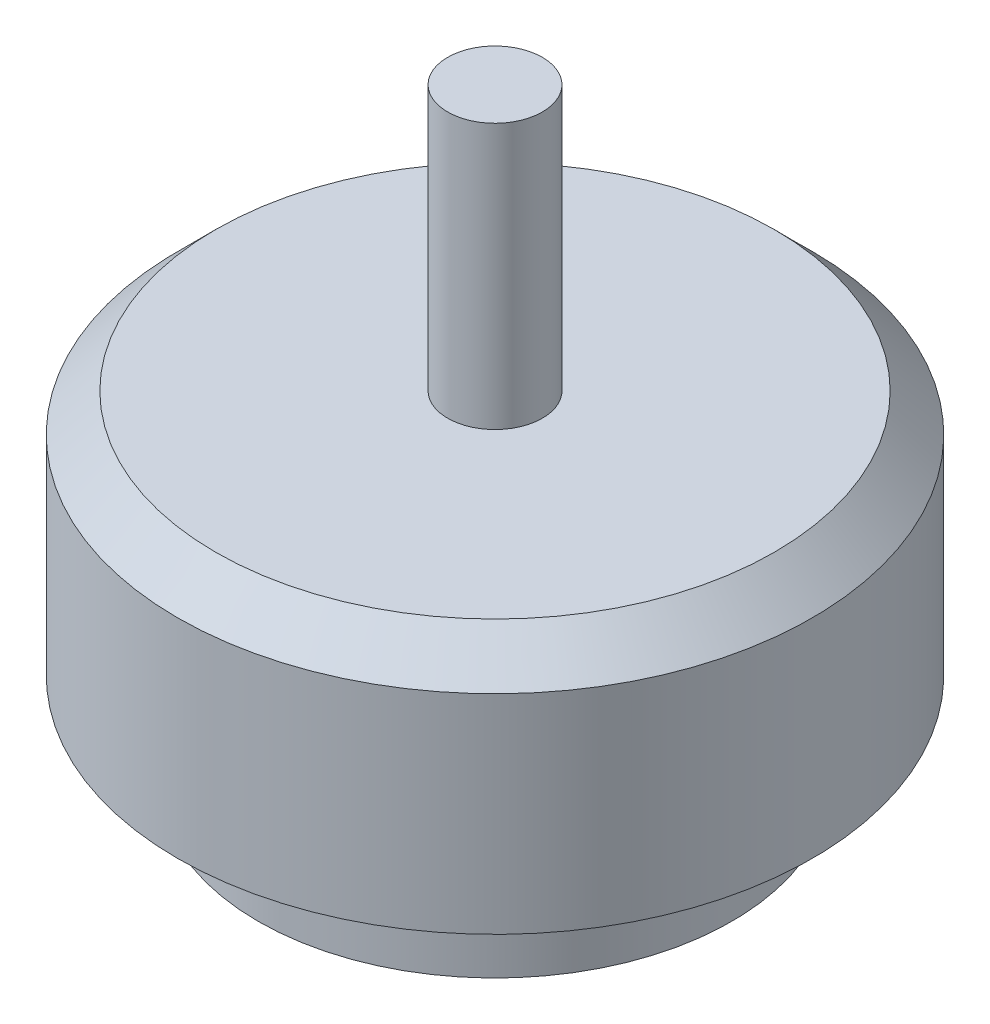
SolidWorks part; units mm, degrees
material "Custom Plastic"
ref_plane "Front Plane" through (0, 0, 0) normal (0, 0, 1) x (1, 0, 0)
ref_plane "Top Plane" through (0, 0, 0) normal (0, 1, 0) x (1, 0, 0)
ref_plane "Right Plane" through (0, 0, 0) normal (1, 0, 0) x (0, 0, -1)
sketch "Sketch1" plane through (0, 0, 0) normal (0, 0, 1) x (1, 0, 0)
  line L0 (0, 14) -> (2.5, 14)
  line L1 (2.5, 14) -> (2.5, 0)
  line L2 (2.5, 0) -> (16.75, 0)
  line L3 (16.75, 0) -> (16.75, -13)
  line L4 (16.75, -13) -> (5, -13)
  line L5 (5, -13) -> (5, -15)
  line L6 (5, -15) -> (12.5, -15)
  line L7 (12.5, -15) -> (12.5, -18)
  line L8 (12.5, -18) -> (0, -18)
  line L9 (0, -18) -> (0, 14) construction
  line L10 (0, 14) -> (0, -18)
  dimension "D1" = 14
  dimension "D2" = 27
  dimension "D3" = 32
  dimension "D4" = 5
  dimension "D5" = 33.5
  dimension "D6" = 25
  dimension "D7" = 2
  dimension "D8" = 10
revolve "Revolve1" add sketch "Sketch1" angle 360 about L9
chamfer "Chamfer1" distance 2 angle 45 1 edges at (0, 0, -16.75)
